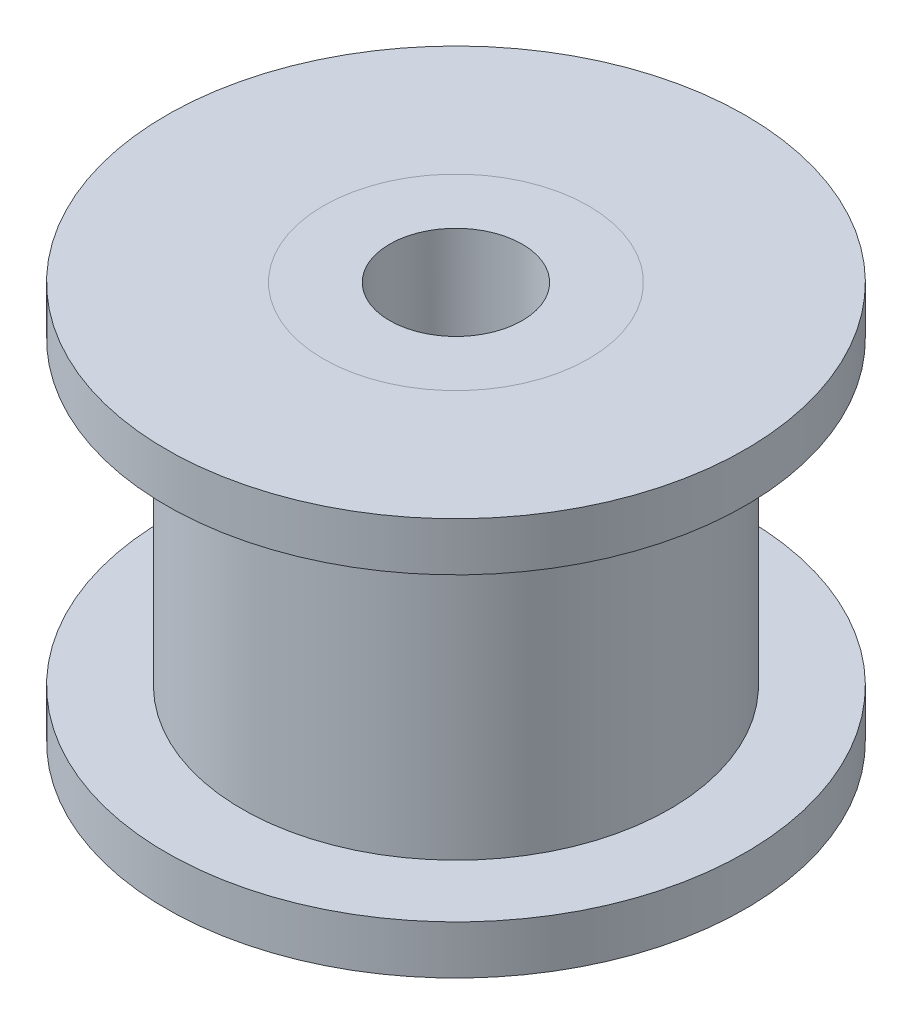
SolidWorks part; units mm, degrees
ref_plane "Plan de face" through (0, 0, 0) normal (0, 0, 1) x (1, 0, 0)
ref_plane "Plan de dessus" through (0, 0, 0) normal (0, 1, 0) x (1, 0, 0)
ref_plane "Plan de droite" through (0, 0, 0) normal (1, 0, 0) x (0, 0, -1)
sketch "Esquisse2" plane through (0, 0, 0) normal (0, 0, 1) x (1, 0, 0)
  line L8 (0, 0) -> (0, 5.8451) construction
  line L10 (2, 1.5) -> (3, 1.5)
  line L11 (3, 1.5) -> (3, 4.5)
  line L12 (3, 4.5) -> (6.55, 4.5)
  line L13 (6.55, 4.5) -> (6.55, 3.4)
  line L14 (6.55, 3.4) -> (4.84, 3.4)
  line L15 (4.84, 3.4) -> (4.84, -3.4)
  line L16 (0, 0) -> (15.8437, 0) construction
  line L17 (6.55, -3.4) -> (4.84, -3.4)
  line L18 (6.55, -4.5) -> (6.55, -3.4)
  line L19 (3, -4.5) -> (6.55, -4.5)
  line L20 (3, -1.5) -> (3, -4.5)
  line L21 (2, -1.5) -> (3, -1.5)
  line L22 (2, 1.5) -> (2, -1.5)
  point P13 (4.84, 0)
  dimension "D1" = 4
  dimension "D2" = 6
  dimension "D3" = 9
  dimension "D4" = 6.8
  dimension "D5" = 13.1
  dimension "D6" = 3
  dimension "D7" = 9.68
revolve "Révolution1" add sketch "Esquisse2" angle 360 about L8
sketch "Esquisse3" plane through (0, -1.5, 0) normal (0, 1, 0) x (1, 0, 0)
  circle A3 centre (0, 0) radius 1.5
  circle A4 centre (0, 0) radius 3 construction
  circle A5 centre (0, 0) radius 3
  dimension "D1" = 3
extrude "Boss.-Extru.1" add sketch "Esquisse3" against normal up to surface (3 mm away) separate body up to face at (0, -4.5, -6.55)
mirror "Symétrie8" about plane through (0, 0, 0) normal (0, 1, 0) of bodies 103
